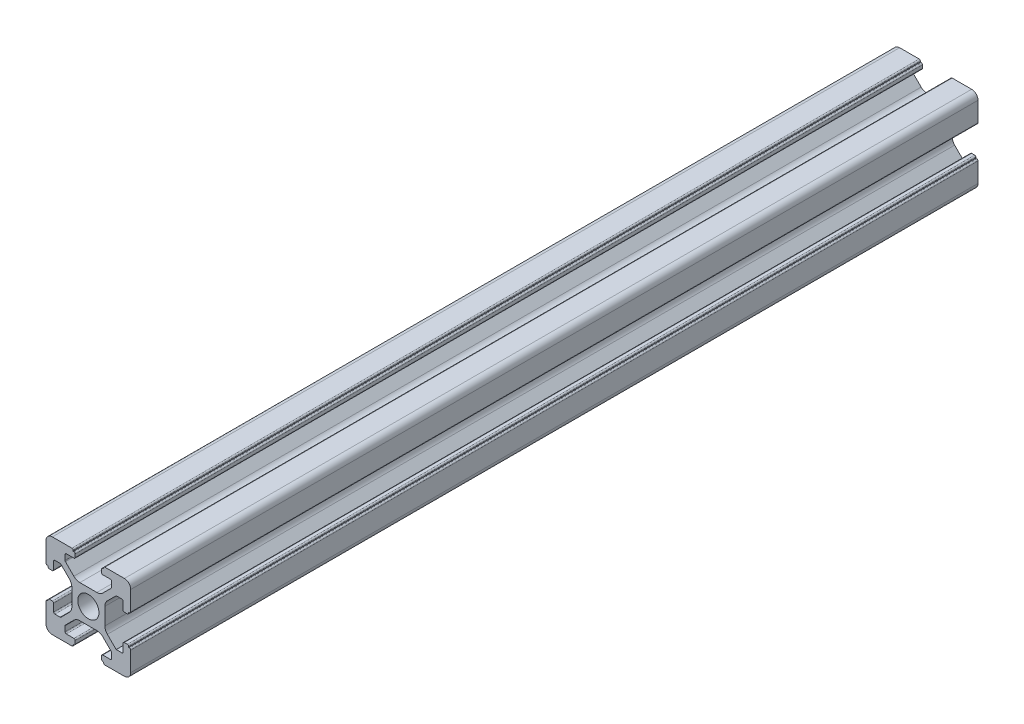
SolidWorks part; units mm, degrees
ref_plane "前视基准面" through (0, 0, 0) normal (0, 0, 1) x (1, 0, 0)
ref_plane "上视基准面" through (0, 0, 0) normal (0, 1, 0) x (1, 0, 0)
ref_plane "右视基准面" through (0, 0, 0) normal (1, 0, 0) x (0, 0, -1)
sketch "草图1" plane through (0, 0, 0) normal (0, 0, 1) x (1, 0, 0)
  line L0 (3.9, 0) -> (3.9, -2.0109)
  line L1 (4.4858, -3.4251) -> (6.5607, -5.5)
  line L2 (6.5607, -5.5) -> (7.9, -5.5)
  line L3 (8.2, -5.2) -> (8.2, -3.4)
  line L4 (8.5, -3.1) -> (9.2, -3.1)
  line L5 (9.5, -3.4) -> (9.5, -3.6)
  line L6 (9.5, -3.6) -> (9.7, -3.6)
  line L7 (10, -3.9) -> (10, -8.5)
  line L8 (8.5, -10) -> (3.9, -10)
  line L9 (3.1, -9.2) -> (3.1, -8.5)
  line L10 (3.4, -8.2) -> (5.2, -8.2)
  line L11 (5.5, -7.9) -> (5.5, -6.6849)
  line L12 (5.4121, -6.4728) -> (3.4251, -4.4858)
  line L13 (2.0109, -3.9) -> (0, -3.9)
  line L14 (0, -3.9) -> (-2.0109, -3.9)
  line L15 (-3.4251, -4.4858) -> (-5.4121, -6.4728)
  line L16 (-5.5, -6.6849) -> (-5.5, -7.9)
  line L17 (-5.2, -8.2) -> (-3.4, -8.2)
  line L18 (-3.1, -8.5) -> (-3.1, -9.2)
  line L19 (-3.9, -10) -> (-8.5, -10)
  line L20 (-10, -8.5) -> (-10, -3.9)
  line L21 (-9.7, -3.6) -> (-9.5, -3.6)
  line L22 (-9.5, -3.6) -> (-9.5, -3.4)
  line L23 (-9.2, -3.1) -> (-8.5, -3.1)
  line L24 (-8.2, -3.4) -> (-8.2, -5.2)
  line L25 (-7.9, -5.5) -> (-6.6849, -5.5)
  line L26 (-6.4728, -5.4121) -> (-4.4858, -3.4251)
  line L27 (-3.9, -2.0109) -> (-3.9, 0)
  line L28 (-3.9, 0) -> (-3.9, 2.0109)
  line L29 (-4.4858, 3.4251) -> (-6.4728, 5.4121)
  line L30 (-6.6849, 5.5) -> (-7.9, 5.5)
  line L31 (-8.2, 5.2) -> (-8.2, 3.4)
  line L32 (-8.5, 3.1) -> (-9.2, 3.1)
  line L33 (-9.5, 3.4) -> (-9.5, 3.6)
  line L34 (-9.5, 3.6) -> (-9.7, 3.6)
  line L35 (-10, 3.9) -> (-10, 8.5)
  line L36 (-8.5, 10) -> (-3.9, 10)
  line L37 (-3.6, 9.7) -> (-3.6, 9.5)
  line L38 (-3.6, 9.5) -> (-3.4, 9.5)
  line L39 (-3.1, 9.2) -> (-3.1, 8.5)
  line L40 (-3.4, 8.2) -> (-5.2, 8.2)
  line L41 (-5.5, 7.9) -> (-5.5, 6.6849)
  line L42 (-5.4121, 6.4728) -> (-3.4251, 4.4858)
  line L43 (-2.0109, 3.9) -> (0, 3.9)
  line L44 (0, 3.9) -> (2.0109, 3.9)
  line L45 (3.4251, 4.4858) -> (5.4121, 6.4728)
  line L46 (5.5, 6.6849) -> (5.5, 7.9)
  line L47 (5.2, 8.2) -> (3.4, 8.2)
  line L48 (3.1, 8.5) -> (3.1, 9.2)
  line L49 (3.4, 9.5) -> (3.6, 9.5)
  line L50 (3.6, 9.5) -> (3.6, 9.7)
  line L51 (3.9, 10) -> (8.5, 10)
  line L52 (10, 8.5) -> (10, 3.9)
  line L53 (9.7, 3.6) -> (9.5, 3.6)
  line L54 (9.5, 3.6) -> (9.5, 3.4)
  line L55 (9.2, 3.1) -> (8.5, 3.1)
  line L56 (8.2, 3.4) -> (8.2, 5.2)
  line L57 (7.9, 5.5) -> (6.6849, 5.5)
  line L58 (6.4728, 5.4121) -> (4.4858, 3.4251)
  line L59 (3.9, 2.0109) -> (3.9, 0)
  circle A0 centre (0, 0) radius 2.5
  arc A1 (3.9, -2.0109) -> (4.4858, -3.4251) centre (5.9, -2.0109) ccw
  arc A2 (7.9, -5.5) -> (8.2, -5.2) centre (7.9, -5.2) ccw
  arc A3 (8.5, -3.1) -> (8.2, -3.4) centre (8.5, -3.4) ccw
  arc A4 (9.5, -3.4) -> (9.2, -3.1) centre (9.2, -3.4) ccw
  arc A5 (10, -3.9) -> (9.7, -3.6) centre (9.7, -3.9) ccw
  arc A6 (8.5, -10) -> (10, -8.5) centre (8.5, -8.5) ccw
  arc A7 (3.6, -9.7) -> (3.9, -10) centre (3.9, -9.7) ccw
  arc A8 (3.6, -9.7) -> (3.4, -9.5) centre (3.4, -9.7) ccw
  arc A9 (3.1, -9.2) -> (3.4, -9.5) centre (3.4, -9.2) ccw
  arc A10 (3.4, -8.2) -> (3.1, -8.5) centre (3.4, -8.5) ccw
  arc A11 (5.2, -8.2) -> (5.5, -7.9) centre (5.2, -7.9) ccw
  arc A12 (5.5, -6.6849) -> (5.4121, -6.4728) centre (5.2, -6.6849) ccw
  arc A13 (3.4251, -4.4858) -> (2.0109, -3.9) centre (2.0109, -5.9) ccw
  arc A14 (-2.0109, -3.9) -> (-3.4251, -4.4858) centre (-2.0109, -5.9) ccw
  arc A15 (-5.4121, -6.4728) -> (-5.5, -6.6849) centre (-5.2, -6.6849) ccw
  arc A16 (-5.5, -7.9) -> (-5.2, -8.2) centre (-5.2, -7.9) ccw
  arc A17 (-3.1, -8.5) -> (-3.4, -8.2) centre (-3.4, -8.5) ccw
  arc A18 (-3.4, -9.5) -> (-3.1, -9.2) centre (-3.4, -9.2) ccw
  arc A19 (-3.4, -9.5) -> (-3.6, -9.7) centre (-3.4, -9.7) ccw
  arc A20 (-3.9, -10) -> (-3.6, -9.7) centre (-3.9, -9.7) ccw
  arc A21 (-10, -8.5) -> (-8.5, -10) centre (-8.5, -8.5) ccw
  arc A22 (-9.7, -3.6) -> (-10, -3.9) centre (-9.7, -3.9) ccw
  arc A23 (-9.2, -3.1) -> (-9.5, -3.4) centre (-9.2, -3.4) ccw
  arc A24 (-8.2, -3.4) -> (-8.5, -3.1) centre (-8.5, -3.4) ccw
  arc A25 (-8.2, -5.2) -> (-7.9, -5.5) centre (-7.9, -5.2) ccw
  arc A26 (-6.6849, -5.5) -> (-6.4728, -5.4121) centre (-6.6849, -5.2) ccw
  arc A27 (-4.4858, -3.4251) -> (-3.9, -2.0109) centre (-5.9, -2.0109) ccw
  arc A28 (-3.9, 2.0109) -> (-4.4858, 3.4251) centre (-5.9, 2.0109) ccw
  arc A29 (-6.4728, 5.4121) -> (-6.6849, 5.5) centre (-6.6849, 5.2) ccw
  arc A30 (-7.9, 5.5) -> (-8.2, 5.2) centre (-7.9, 5.2) ccw
  arc A31 (-8.5, 3.1) -> (-8.2, 3.4) centre (-8.5, 3.4) ccw
  arc A32 (-9.5, 3.4) -> (-9.2, 3.1) centre (-9.2, 3.4) ccw
  arc A33 (-10, 3.9) -> (-9.7, 3.6) centre (-9.7, 3.9) ccw
  arc A34 (-8.5, 10) -> (-10, 8.5) centre (-8.5, 8.5) ccw
  arc A35 (-3.6, 9.7) -> (-3.9, 10) centre (-3.9, 9.7) ccw
  arc A36 (-3.1, 9.2) -> (-3.4, 9.5) centre (-3.4, 9.2) ccw
  arc A37 (-3.4, 8.2) -> (-3.1, 8.5) centre (-3.4, 8.5) ccw
  arc A38 (-5.2, 8.2) -> (-5.5, 7.9) centre (-5.2, 7.9) ccw
  arc A39 (-5.5, 6.6849) -> (-5.4121, 6.4728) centre (-5.2, 6.6849) ccw
  arc A40 (-3.4251, 4.4858) -> (-2.0109, 3.9) centre (-2.0109, 5.9) ccw
  arc A41 (2.0109, 3.9) -> (3.4251, 4.4858) centre (2.0109, 5.9) ccw
  arc A42 (5.4121, 6.4728) -> (5.5, 6.6849) centre (5.2, 6.6849) ccw
  arc A43 (5.5, 7.9) -> (5.2, 8.2) centre (5.2, 7.9) ccw
  arc A44 (3.1, 8.5) -> (3.4, 8.2) centre (3.4, 8.5) ccw
  arc A45 (3.4, 9.5) -> (3.1, 9.2) centre (3.4, 9.2) ccw
  arc A46 (3.9, 10) -> (3.6, 9.7) centre (3.9, 9.7) ccw
  arc A47 (10, 8.5) -> (8.5, 10) centre (8.5, 8.5) ccw
  arc A48 (9.7, 3.6) -> (10, 3.9) centre (9.7, 3.9) ccw
  arc A49 (9.2, 3.1) -> (9.5, 3.4) centre (9.2, 3.4) ccw
  arc A50 (8.2, 3.4) -> (8.5, 3.1) centre (8.5, 3.4) ccw
  arc A51 (8.2, 5.2) -> (7.9, 5.5) centre (7.9, 5.2) ccw
  arc A52 (6.6849, 5.5) -> (6.4728, 5.4121) centre (6.6849, 5.2) ccw
  arc A53 (4.4858, 3.4251) -> (3.9, 2.0109) centre (5.9, 2.0109) ccw
extrude "凸台-拉伸1" add sketch "草图1" along normal blind 200 contours L42 A40 L43 L44 A41 L45 A42 L46 A43 L47 A44 L48 A45 L49 L50 A46 L51 A47 L52 A48 L53 L54 A49 L55 A50 L56 A51 L57 A52 L58 A53 L59 L0 A1 L1 L2 A2 L3 A3 L4 A4 L5 L6 A5 L7 A6 L8 A7 A8 A9 L9 A10 L10 A11 L11 A12 L12 A13 L13 L14 A14 L15 A15 L16 A16 L17 A17 L18 A18 A19 A20 L19 A21 L20 A22 L21 L22 A23 L23 A24 L24 A25 L25 A26 L26 A27 L27 L28 A28 L29 A29 L30 A30 L31 A31 L32 A32 L33 L34 A33 L35 A34 L36 A35 L37 L38 A36 L39 A37 L40 A38 L41 A39 | A0
